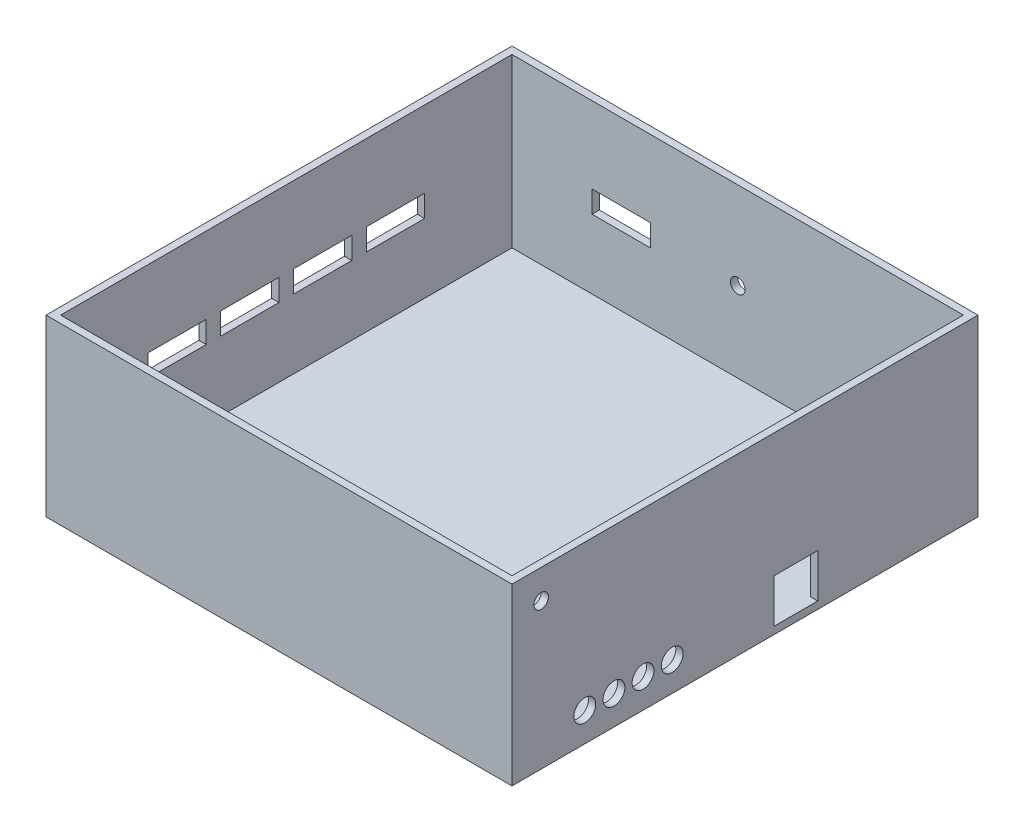
SolidWorks part; units mm, degrees
ref_plane "Front Plane" through (0, 0, 0) normal (0, 0, 1) x (1, 0, 0)
ref_plane "Top Plane" through (0, 0, 0) normal (0, 1, 0) x (1, 0, 0)
ref_plane "Right Plane" through (0, 0, 0) normal (1, 0, 0) x (0, 0, -1)
sketch "Sketch1" plane through (0, 0, 0) normal (0, 1, 0) x (1, 0, 0)
  line L1 (-101.6, -101.6) -> (101.6, -101.6)
  line L2 (-101.6, -101.6) -> (-101.6, 101.6)
  line L3 (-101.6, 101.6) -> (101.6, 101.6)
  line L4 (101.6, -101.6) -> (101.6, 101.6)
  line L5 (-101.6, -101.6) -> (101.6, 101.6) construction
  line L6 (-101.6, 101.6) -> (101.6, -101.6) construction
  point P0 (0, 0)
  dimension "D1" = 203.2
  dimension "D2" = 203.2
extrude "Boss-Extrude1" add sketch "Sketch1" along normal blind 76.2
sketch "Sketch2" plane through (0, 76.2, 0) normal (0, 1, 0) x (1, 0, 0)
  line L0 (101.6, 101.6) -> (-101.6, 101.6) construction
  line L1 (-98.425, -98.425) -> (98.425, -98.425)
  line L2 (-98.425, -98.425) -> (-98.425, 98.425)
  line L3 (-98.425, 98.425) -> (98.425, 98.425)
  line L4 (98.425, -98.425) -> (98.425, 98.425)
  line L5 (-98.425, -98.425) -> (98.425, 98.425) construction
  line L6 (-98.425, 98.425) -> (98.425, -98.425) construction
  line L8 (-101.6, 101.6) -> (-101.6, -101.6) construction
  point P0 (0, 0)
  dimension "D1" = 3.175
  dimension "D2" = 3.175
extrude "Cut-Extrude1" cut sketch "Sketch2" against normal blind 73.025
sketch "Sketch3" plane through (101.6, 0, 0) normal (1, 0, 0) x (0, 0, -1)
  line L0 (-101.6, 76.2) -> (-101.6, 0) construction
  line L1 (-101.6, 0) -> (101.6, 0) construction
  line L2 (-101.6, 76.2) -> (101.6, 76.2) construction
  line L3 (101.6, 76.2) -> (101.6, 0) construction
  line L4 (31.75, 22.225) -> (12.7, 22.225)
  line L5 (31.75, 22.225) -> (31.75, 3.175)
  line L6 (31.75, 3.175) -> (12.7, 3.175)
  line L7 (12.7, 22.225) -> (12.7, 3.175)
  line L8 (31.75, 22.225) -> (12.7, 3.175) construction
  line L9 (31.75, 3.175) -> (12.7, 22.225) construction
  circle A3 centre (-69.85, 12.7) radius 4.7625
  circle A4 centre (-57.15, 12.7) radius 4.7625
  circle A5 centre (-44.45, 12.7) radius 4.7625
  circle A6 centre (-31.75, 12.7) radius 4.7625
  circle A7 centre (-88.9, 63.5) radius 3.175
  point P4 (22.225, 12.7)
  dimension "D1" = 9.525
  dimension "D2" = 12.7
  dimension "D3" = 4
  dimension "D6" = 19.05
  dimension "D4" = 44.45
  dimension "D5" = 12.7
  dimension "D10" = 6.35
  dimension "D11" = 12.7
  dimension "D12" = 12.7
  dimension "D7" = 69.85
  dimension "D8" = 3.175
  dimension "D9" = 19.05
extrude "Cut-Extrude2" cut sketch "Sketch3" against normal up to next and the other way through all
sketch "Sketch4" plane through (0, 0, -101.6) normal (0, 0, -1) x (-1, 0, 0)
  line L0 (-101.6, 38.1) -> (101.6, 38.1) construction
  line L1 (38.1, 33.3375) -> (63.5, 33.3375)
  line L2 (38.1, 33.3375) -> (38.1, 42.8625)
  line L3 (38.1, 42.8625) -> (63.5, 42.8625)
  line L4 (63.5, 33.3375) -> (63.5, 42.8625)
  line L5 (38.1, 33.3375) -> (63.5, 42.8625) construction
  line L6 (38.1, 42.8625) -> (63.5, 33.3375) construction
  line L9 (-101.6, 76.2) -> (-101.6, 0) construction
  line L10 (101.6, 76.2) -> (101.6, 0) construction
  circle A0 centre (0, 38.1) radius 3.175
  point P0 (50.8, 38.1)
  dimension "D4" = 6.35
  dimension "D1" = 25.4
  dimension "D2" = 9.525
  dimension "D3" = 38.1
extrude "Cut-Extrude3" cut sketch "Sketch4" against normal up to next
sketch "Sketch5" plane through (-101.6, 0, 0) normal (-1, 0, 0) x (0, 0, 1)
  line L0 (-101.6, 38.1) -> (101.6, 38.1) construction
  line L1 (-101.6, 76.2) -> (-101.6, 0) construction
  line L2 (101.6, 76.2) -> (101.6, 0) construction
  line L4 (-28.575, 33.3375) -> (-3.175, 33.3375)
  line L5 (-28.575, 33.3375) -> (-28.575, 42.8625)
  line L6 (-28.575, 42.8625) -> (-3.175, 42.8625)
  line L7 (-3.175, 33.3375) -> (-3.175, 42.8625)
  line L8 (-28.575, 33.3375) -> (-3.175, 42.8625) construction
  line L9 (-28.575, 42.8625) -> (-3.175, 33.3375) construction
  line L21 (-60.325, 33.3375) -> (-60.325, 42.8625)
  line L22 (-60.325, 33.3375) -> (-34.925, 33.3375)
  line L23 (0, 0) -> (0, 76.2) construction
  line L24 (-101.6, 0) -> (101.6, 0) construction
  line L25 (-101.6, 76.2) -> (101.6, 76.2) construction
  line L26 (-34.925, 33.3375) -> (-34.925, 42.8625)
  line L27 (-60.325, 42.8625) -> (-34.925, 42.8625)
  line L28 (60.325, 33.3375) -> (34.925, 33.3375)
  line L29 (34.925, 33.3375) -> (34.925, 42.8625)
  line L30 (60.325, 42.8625) -> (34.925, 42.8625)
  line L31 (60.325, 33.3375) -> (60.325, 42.8625)
  line L32 (28.575, 42.8625) -> (3.175, 42.8625)
  line L33 (3.175, 33.3375) -> (3.175, 42.8625)
  line L34 (28.575, 33.3375) -> (3.175, 33.3375)
  line L35 (28.575, 33.3375) -> (28.575, 42.8625)
  point P6 (-15.875, 38.1)
  point P32 (40.3421, 35.6959)
  dimension "D1" = 9.525
  dimension "D2" = 25.4
  dimension "D4" = 2
  dimension "D5" = 33.3375
  dimension "D3" = 3.175
  dimension "D6" = 41.275
extrude "Cut-Extrude4" cut sketch "Sketch5" against normal up to next
